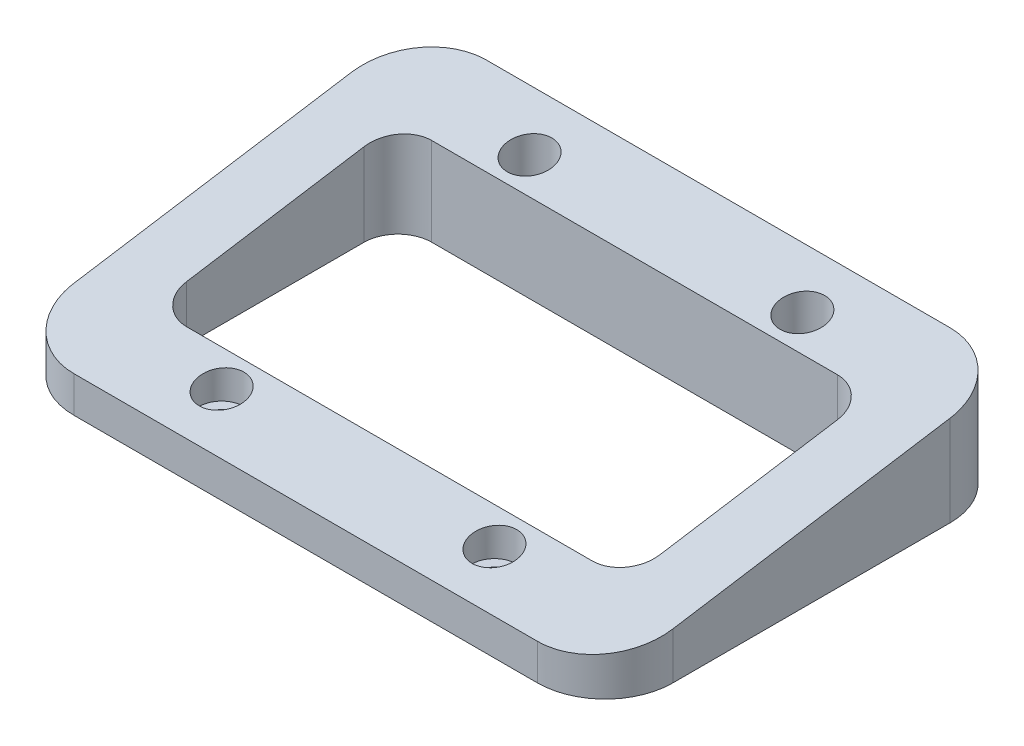
SolidWorks part; units mm, degrees
material "ABS"
ref_plane "Front Plane" through (0, 0, 0) normal (0, 0, 1) x (1, 0, 0)
ref_plane "Top Plane" through (0, 0, 0) normal (0, 1, 0) x (1, 0, 0)
ref_plane "Right Plane" through (0, 0, 0) normal (1, 0, 0) x (0, 0, -1)
sketch "Sketch2" plane through (0, 0, 0) normal (0, 1, 0) x (1, 0, 0)
  line L0 (41.9548, -23.6119) -> (52.1148, -23.6119) construction
  line L1 (12.3798, 24.2181) -> (40.6848, 24.2181) construction
  line L2 (11.1098, 22.9481) -> (11.1098, 22.3881) construction
  line L3 (12.3798, 21.1181) -> (40.6848, 21.1181) construction
  line L4 (82.9598, 22.9481) -> (82.9598, 22.3881)
  line L5 (82.9598, -23.8919) -> (82.9598, -23.3319)
  line L14 (41.9548, 22.9481) -> (41.9548, 22.3881) construction
  line L15 (52.1148, 22.9481) -> (52.1148, 22.3881)
  line L16 (53.3848, 24.2181) -> (81.6898, 24.2181)
  line L17 (53.3848, 21.1181) -> (81.6898, 21.1181)
  line L18 (53.3848, -22.0619) -> (81.6898, -22.0619)
  line L19 (53.3848, -25.1619) -> (81.6898, -25.1619)
  line L20 (52.1148, -23.8919) -> (52.1148, -23.3319)
  line L21 (41.9548, -23.8919) -> (41.9548, -23.3319)
  line L22 (12.3798, -22.0619) -> (40.6848, -22.0619)
  line L23 (11.1098, -23.8919) -> (11.1098, -23.3319)
  line L24 (12.3798, -25.1619) -> (40.6848, -25.1619)
  line L25 (41.9548, 22.6681) -> (52.1148, 22.6681) construction
  line L26 (47.0348, 22.6681) -> (47.0348, -23.6119) construction
  line L27 (11.1098, -23.6119) -> (41.9548, -23.6119) construction
  line L28 (81.8748, 30.5281) -> (12.1948, 30.5281)
  line L29 (92.0348, 20.3681) -> (92.0348, -21.3119)
  line L30 (81.8748, -31.4719) -> (12.1948, -31.4719)
  line L31 (2.0348, 20.3681) -> (2.0348, -21.3119)
  line L32 (92.0348, 30.5281) -> (2.0348, -31.4719) construction
  line L33 (92.0348, -31.4719) -> (2.0348, 30.5281) construction
  line L34 (16.5548, 17.9431) -> (77.5148, 17.9431)
  line L35 (11.4748, 12.8631) -> (11.4748, -13.8069)
  line L36 (16.5548, -18.8869) -> (77.5148, -18.8869)
  line L37 (82.5948, 12.8631) -> (82.5948, -13.8069)
  line L38 (11.4748, 17.9431) -> (82.5948, -18.8869) construction
  line L39 (11.4748, -18.8869) -> (82.5948, 17.9431) construction
  line L40 (52.1148, -23.6119) -> (82.9598, -23.6119) construction
  line L41 (26.5323, -25.1619) -> (26.5323, -22.0619) construction
  line L42 (67.5373, -25.1619) -> (67.5373, -22.0619) construction
  line L43 (11.4748, -0.4719) -> (82.5948, -0.4719) construction
  line L44 (11.1098, 22.6681) -> (41.9548, 22.6681) construction
  line L45 (26.5323, 24.2181) -> (26.5323, 21.1181) construction
  line L46 (52.1148, 22.6681) -> (82.9598, 22.6681) construction
  line L47 (67.5373, 24.2181) -> (67.5373, 21.1181) construction
  arc A0 (11.1098, 22.9481) -> (12.3798, 24.2181) centre (12.3798, 22.9481) cw construction
  arc A6 (11.1098, 22.3881) -> (12.3798, 21.1181) centre (12.3798, 22.3881) ccw construction
  arc A7 (82.9598, 22.9481) -> (81.6898, 24.2181) centre (81.6898, 22.9481) ccw
  arc A8 (81.6898, 21.1181) -> (82.9598, 22.3881) centre (81.6898, 22.3881) ccw
  arc A9 (40.6848, 24.2181) -> (41.9548, 22.9481) centre (40.6848, 22.9481) cw construction
  arc A10 (41.9548, 22.3881) -> (40.6848, 21.1181) centre (40.6848, 22.3881) cw construction
  arc A19 (52.1148, 22.3881) -> (53.3848, 21.1181) centre (53.3848, 22.3881) ccw
  arc A20 (52.1148, 22.9481) -> (53.3848, 24.2181) centre (53.3848, 22.9481) cw
  arc A21 (82.9598, -23.8919) -> (81.6898, -25.1619) centre (81.6898, -23.8919) cw
  arc A22 (81.6898, -22.0619) -> (82.9598, -23.3319) centre (81.6898, -23.3319) cw
  arc A23 (52.1148, -23.3319) -> (53.3848, -22.0619) centre (53.3848, -23.3319) cw
  arc A24 (52.1148, -23.8919) -> (53.3848, -25.1619) centre (53.3848, -23.8919) ccw
  arc A25 (40.6848, -25.1619) -> (41.9548, -23.8919) centre (40.6848, -23.8919) ccw
  arc A26 (41.9548, -23.3319) -> (40.6848, -22.0619) centre (40.6848, -23.3319) ccw
  arc A27 (11.1098, -23.3319) -> (12.3798, -22.0619) centre (12.3798, -23.3319) cw
  arc A28 (11.1098, -23.8919) -> (12.3798, -25.1619) centre (12.3798, -23.8919) ccw
  arc A29 (2.0348, 20.3681) -> (12.1948, 30.5281) centre (12.1948, 20.3681) cw
  arc A30 (12.1948, -31.4719) -> (2.0348, -21.3119) centre (12.1948, -21.3119) cw
  arc A31 (92.0348, -21.3119) -> (81.8748, -31.4719) centre (81.8748, -21.3119) cw
  arc A32 (92.0348, 20.3681) -> (81.8748, 30.5281) centre (81.8748, 20.3681) ccw
  arc A33 (11.4748, 12.8631) -> (16.5548, 17.9431) centre (16.5548, 12.8631) cw
  arc A34 (16.5548, -18.8869) -> (11.4748, -13.8069) centre (16.5548, -13.8069) cw
  arc A35 (82.5948, -13.8069) -> (77.5148, -18.8869) centre (77.5148, -13.8069) cw
  arc A36 (77.5148, 17.9431) -> (82.5948, 12.8631) centre (77.5148, 12.8631) cw
  circle A37 centre (67.5373, 22.6681) radius 1.65 construction
  circle A38 centre (26.5323, 22.6681) radius 1.65 construction
  circle A39 centre (26.5323, -23.6119) radius 1.65 construction
  circle A40 centre (67.5373, -23.6119) radius 1.65 construction
  point P3 (41.9548, -23.6119)
  point P11 (47.0348, -0.4719)
  point P73 (47.0348, -0.4719)
  dimension "D5" = 10.16
  dimension "D7" = 28.305
  dimension "D9" = 28.305
  dimension "D11" = 90
  dimension "D21" = 1.27
  dimension "D22" = 1.27
  dimension "D23" = 1.27
  dimension "D24" = 1.27
  dimension "D25" = 1.27
  dimension "D26" = 1.27
  dimension "D27" = 1.27
  dimension "D28" = 1.27
  dimension "D12" = 10.16
  dimension "D13" = 10.16
  dimension "D14" = 10.16
  dimension "D15" = 10.16
  dimension "D18" = 5.08
  dimension "D20" = 5.08
  dimension "D29" = 5.08
  dimension "D30" = 5.08
  dimension "D31" = 3.3
  dimension "D32" = 3.3
  dimension "D3" = 43.18
  dimension "D4" = 10.16
  dimension "D6" = 28.305
  dimension "D8" = 28.305
  dimension "D10" = 62
  dimension "D16" = 36.83
  dimension "D17" = 71.12
  dimension "D19" = 3.1
extrude "Boss-Extrude1" add sketch "Sketch2" along normal blind 15.24 contours A32 L28 A29 L31 A30 L30 A31 L29 | A34 L36 A35 L37 A36 L34 A33 L35
sketch "Sketch3" plane through (2.0348, 0, 0) normal (-1, 0, 0) x (0, 0, 1)
  line L4 (-20.3681, 0) -> (21.3119, 0)
  line L5 (21.3119, 0) -> (21.3119, 15.24)
  line L6 (21.3119, 15.24) -> (-20.3681, 15.24)
  line L7 (-20.3681, 15.24) -> (-20.3681, 0)
  line L10 (21.3119, 15.24) -> (-20.3681, 15.24)
  line L14 (-20.3681, 15.24) -> (-30.5281, 15.24) construction
  line L22 (-20.3681, 15.24) -> (-30.5281, 15.24)
  line L24 (-30.5281, 15.24) -> (31.4719, 5.4202)
  line L25 (31.4719, 15.24) -> (31.4719, 0) construction
  line L26 (31.4719, 15.24) -> (21.3119, 15.24) construction
  line L27 (31.4719, 15.24) -> (31.4719, 5.4202)
  line L28 (31.4719, 15.24) -> (21.3119, 15.24)
  dimension "D2" = 9
  dimension "D1" = 0
extrude "Cut-Extrude1" cut sketch "Sketch3" against normal through all
ref_plane "Plane1" through (0, 4.37, 0) normal (0, -1, 0) x (-1, 0, 0)
sketch "Sketch13" plane through (0, 4.37, 0) normal (0, -1, 0) x (-1, 0, 0)
  circle A0 centre (-67.5373, -23.6119) radius 1.65 construction
  circle A1 centre (-26.5323, -23.6119) radius 1.65 construction
  circle A2 centre (-26.5323, 22.6681) radius 1.65 construction
  circle A3 centre (-67.5373, 22.6681) radius 1.65 construction
  circle A4 centre (-67.5373, -23.6119) radius 1.65
  circle A5 centre (-26.5323, -23.6119) radius 1.65
  circle A6 centre (-26.5323, 22.6681) radius 1.65
  circle A7 centre (-67.5373, 22.6681) radius 1.65
hole_wizard "CBORE for M3 SBHCS2" positions "Sketch14" profile "Sketch15" counterbore size "M3" standard "ANSI Metric"
sketch "Sketch14" plane through (0, 4.37, 0) normal (0, -1, 0) x (-1, 0, 0)
  point P0 (-67.5373, -23.6119)
  point P3 (-26.5323, -23.6119)
  point P6 (-26.5323, 22.6681)
  point P9 (-67.5373, 22.6681)
sketch "Sketch15" plane through (67.5373, 4.37, 23.6119) normal (1, 0, 0) x (0, 0, 1)
  line L0 (0, 0) -> (0, 4.37)
  line L1 (0, 4.37) -> (1.8, 4.37)
  line L3 (1.8, 4.37) -> (1.8, 1.65)
  line L4 (1.8, 1.65) -> (3.35, 1.65)
  line L5 (3.35, 1.65) -> (3.35, 0)
  line L7 (3.35, 0) -> (0, 0)
  line L11 (0, -6.35) -> (0, 107.95) construction
  dimension "Thru Hole Dia." = 3.6
  dimension "Thru Hole Depth" = 4.37
  dimension "C'Bore Dia." = 6.7
  dimension "C'Bore Depth" = 1.65
sketch "Sketch16" plane through (0, 4.37, 0) normal (0, -1, 0) x (-1, 0, 0)
  circle A0 centre (-26.5323, -23.6119) radius 3.35 construction
  circle A1 centre (-67.5373, -23.6119) radius 3.35
  circle A2 centre (-67.5373, -23.6119) radius 3.35
  circle A3 centre (-67.5373, 22.6681) radius 3.35 construction
  circle A4 centre (-26.5323, 22.6681) radius 3.35 construction
  circle A5 centre (-26.5323, -23.6119) radius 3.35
  circle A6 centre (-67.5373, 22.6681) radius 3.35
  circle A7 centre (-26.5323, 22.6681) radius 3.35
  dimension "D1" = 0
extrude "Cut-Extrude2" cut sketch "Sketch16" against normal through all
